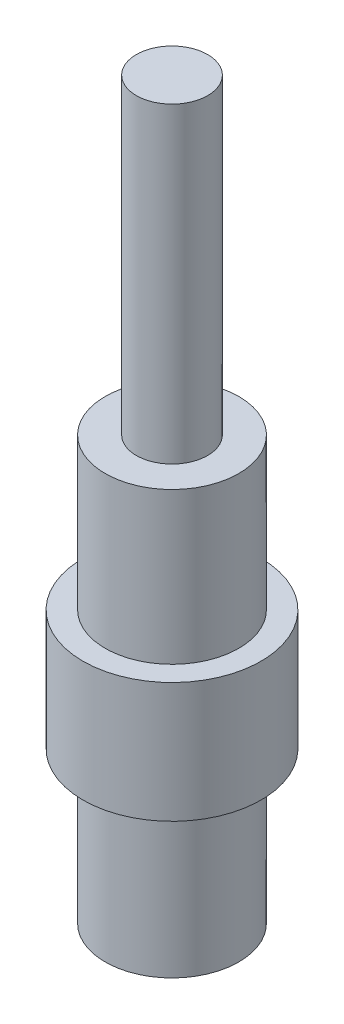
SolidWorks part; units mm, degrees
material "3.1325 (EN-AW 2017A)"
ref_plane "Płaszczyzna przednia" through (0, 0, 0) normal (0, 0, 1) x (1, 0, 0)
ref_plane "Płaszczyzna górna" through (0, 0, 0) normal (0, 1, 0) x (1, 0, 0)
ref_plane "Płaszczyzna prawa" through (0, 0, 0) normal (1, 0, 0) x (0, 0, -1)
sketch "Szkic1" plane through (0, 0, 0) normal (0, 0, 1) x (1, 0, 0)
  line L0 (0, 0) -> (0, 47.5) construction
  line L1 (4, 47.5) -> (7.5, 47.5)
  line L2 (7.5, 30.5) -> (10, 30.5)
  line L3 (10, 30.5) -> (10, 17)
  line L4 (10, 17) -> (7.5, 17)
  line L5 (7.5, 47.5) -> (7.5, 30.5)
  line L6 (7.5, 17) -> (7.5, 0)
  line L7 (7.5, 0) -> (0, 0)
  line L8 (0, 0) -> (0, 47.5)
  line L9 (4, 47.5) -> (4, 82.5)
  line L10 (4, 82.5) -> (0, 82.5)
  line L11 (0, 82.5) -> (0, 47.5)
  dimension "D1" = 17
  dimension "D2" = 13.5
  dimension "D3" = 10
  dimension "D4" = 7.5
  dimension "D5" = 17
  dimension "D6" = 4
  dimension "D7" = 35
revolve "Obrót1" add sketch "Szkic1" angle 360 about L0
